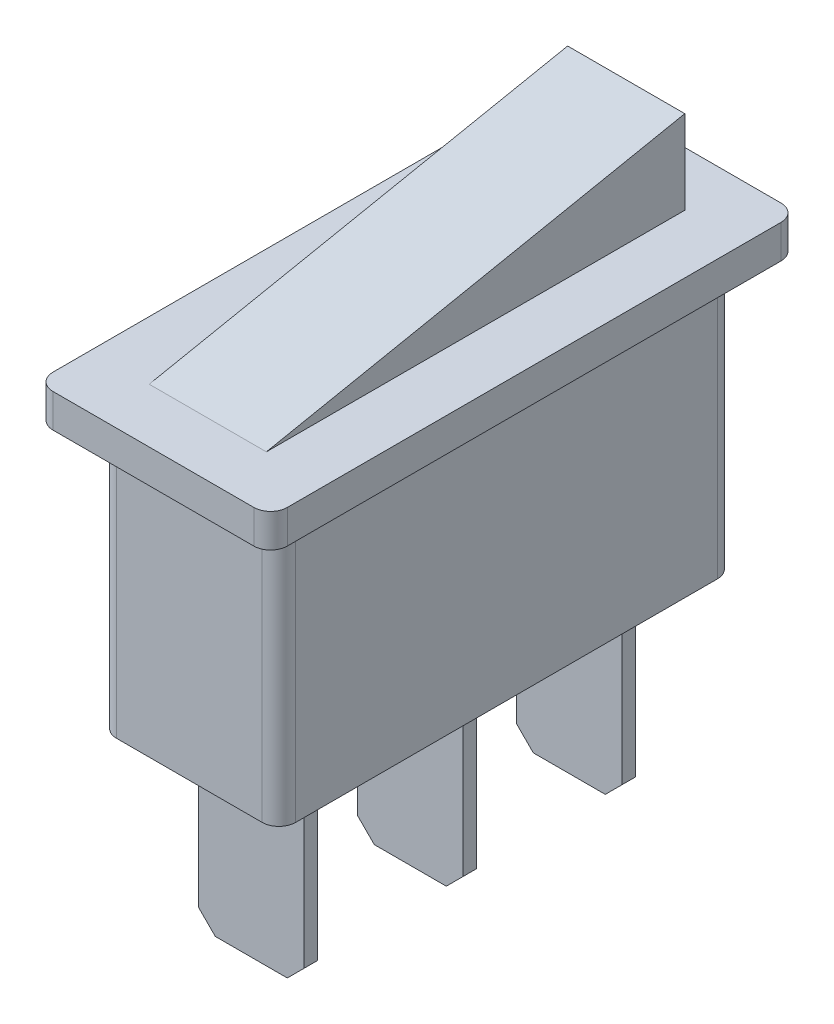
SolidWorks part; units mm, degrees
ref_plane "Ebene vorne" through (0, 0, 0) normal (0, 0, 1) x (1, 0, 0)
ref_plane "Ebene oben" through (0, 0, 0) normal (0, 1, 0) x (1, 0, 0)
ref_plane "Ebene rechts" through (0, 0, 0) normal (1, 0, 0) x (0, 0, -1)
sketch "Skizze1" plane through (0, 0, 0) normal (0, 1, 0) x (1, 0, 0)
  line L1 (0, 0) -> (14, 0)
  line L2 (0, 0) -> (0, 31.5)
  line L3 (0, 31.5) -> (14, 31.5)
  line L4 (14, 0) -> (14, 31.5)
  dimension "D1" = 14
  dimension "D2" = 31.5
extrude "Aufsatz-Linear austragen1" add sketch "Skizze1" along normal blind 2
fillet "Verrundung1" radius 1 4 edges at (0, 1, -31.5) (14, 1, -31.5) (14, 1, 0) (0, 1, 0)
sketch "Skizze2" plane through (0, 0, 0) normal (0, -1, 0) x (1, 0, 0)
  line L0 (7, 0) -> (7, -31.5) construction
  line L1 (1, 0) -> (13, 0) construction
  line L2 (13, -31.5) -> (1, -31.5) construction
  line L3 (14, -15.75) -> (0, -15.75) construction
  line L4 (14, -1) -> (14, -30.5) construction
  line L5 (0, -30.5) -> (0, -1) construction
  line L7 (12.35, -2.15) -> (1.65, -2.15)
  line L8 (12.35, -2.15) -> (12.35, -29.35)
  line L9 (12.35, -29.35) -> (1.65, -29.35)
  line L10 (1.65, -2.15) -> (1.65, -29.35)
  dimension "D1" = 10.7
  dimension "D2" = 27.2
extrude "Aufsatz-Linear austragen2" add sketch "Skizze2" along normal blind 16.2
fillet "Verrundung2" radius 1 4 edges at (1.65, -8.1, -29.35) (1.65, -8.1, -2.15) (12.35, -8.1, -2.15) (12.35, -8.1, -29.35)
sketch "Skizze3" plane through (0, -16.2, 0) normal (0, -1, 0) x (1, 0, 0)
  line L0 (7, -2.15) -> (7, -29.35) construction
  line L1 (11.35, -2.15) -> (2.65, -2.15) construction
  line L2 (2.65, -29.35) -> (11.35, -29.35) construction
  line L3 (1.65, -15.75) -> (12.35, -15.75) construction
  line L4 (1.65, -3.15) -> (1.65, -28.35) construction
  line L5 (12.35, -28.35) -> (12.35, -3.15) construction
  line L7 (3.85, -15.35) -> (10.15, -15.35)
  line L8 (3.85, -15.35) -> (3.85, -16.15)
  line L9 (3.85, -16.15) -> (10.15, -16.15)
  line L10 (10.15, -15.35) -> (10.15, -16.15)
  dimension "D1" = 6.3
  dimension "D2" = 0.8
extrude "Aufsatz-Linear austragen3" add sketch "Skizze3" along normal blind 11
pattern_linear "Lineares Muster1" count 2 spacing 9.5 along (0, 0, -1) count 2 spacing 9.5 along (0, 0, 1) of "Aufsatz-Linear austragen3"
sketch "Skizze4" plane through (0, 0, -5.85) normal (0, 0, 1) x (1, 0, 0)
  line L0 (7, -27.2) -> (7, -16.2) construction
  line L1 (10.15, -27.2) -> (3.85, -27.2) construction
  line L2 (10.15, -16.2) -> (3.85, -16.2) construction
  line L3 (3.85, -26.2) -> (3.85, -27.2)
  line L4 (3.85, -27.2) -> (3.85, -16.2) construction
  line L5 (3.85, -27.2) -> (4.85, -27.2)
  line L6 (4.85, -27.2) -> (3.85, -26.2)
  line L7 (9.15, -27.2) -> (10.15, -26.2)
  line L8 (10.15, -27.2) -> (9.15, -27.2)
  line L9 (10.15, -26.2) -> (10.15, -27.2)
  dimension "D1" = 1
  dimension "D2" = 1
extrude "Schnitt-Linear austragen1" cut sketch "Skizze4" against normal through all
ref_plane "Ebene1" through (7, 0, 0) normal (1, 0, 0) x (0, 0, -1)
sketch "Skizze5" plane through (7, 0, 0) normal (1, 0, 0) x (0, 0, -1)
  line L0 (3.25, 2) -> (28.25, 7)
  line L1 (1, 2) -> (30.5, 2) construction
  line L2 (28.25, 7) -> (28.25, 2)
  line L3 (28.25, 2) -> (3.25, 2)
  line L4 (15.75, 0) -> (15.75, 6.8828) construction
  line L5 (1, 0) -> (30.5, 0) construction
  point P9 (0, 0)
  point P10 (0, 0)
  dimension "D1" = 25
  dimension "D2" = 5
extrude "Aufsatz-Linear austragen4" add sketch "Skizze5" along normal blind 3.5 and the other way blind 3.5
